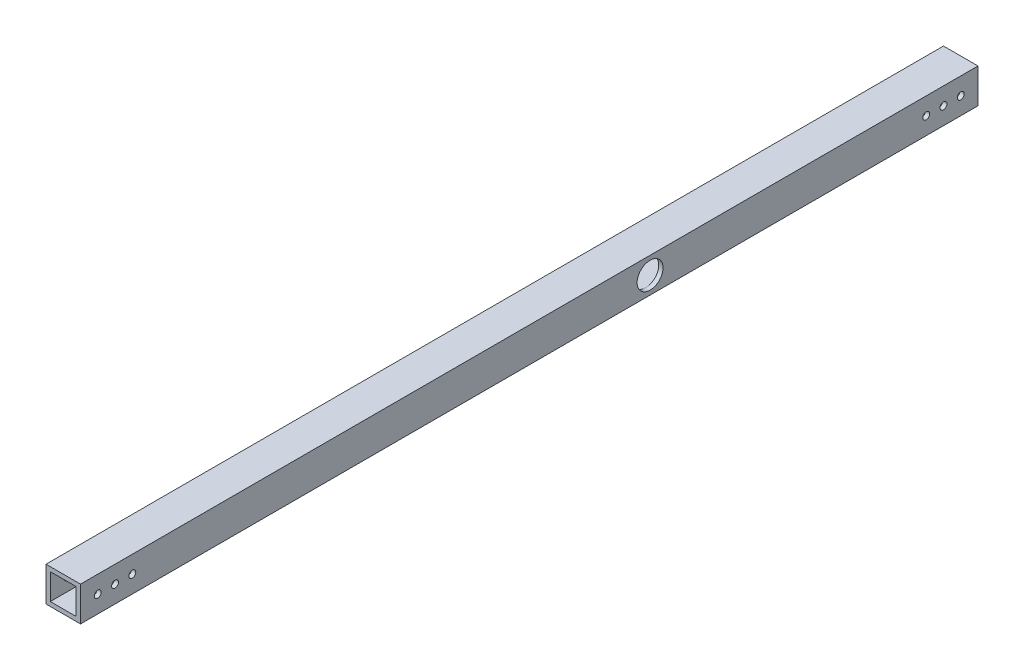
SolidWorks part; units mm, degrees
material "6061 Alloy"
ref_plane "Front" through (0, 0, 0) normal (0, 0, 1) x (1, 0, 0)
ref_plane "Top" through (0, 0, 0) normal (0, 1, 0) x (1, 0, 0)
ref_plane "Right" through (0, 0, 0) normal (1, 0, 0) x (0, 0, -1)
sketch "Sketch1" plane through (0, 0, 0) normal (0, 0, 1) x (1, 0, 0)
  line L1 (0, 0) -> (-25.4, 0)
  line L2 (0, 0) -> (0, 25.4)
  line L3 (0, 25.4) -> (-25.4, 25.4)
  line L4 (-25.4, 0) -> (-25.4, 25.4)
  dimension "D1" = 25.4
extrude "Extrude-Thin1" add sketch "Sketch1" along normal blind 660.4 thin
sketch "Sketch4" plane through (-25.4, 0, 0) normal (-1, 0, 0) x (0, 0, 1)
  line L0 (0, 25.4) -> (0, 0) construction
  line L1 (660.4, 0) -> (0, 0) construction
  circle A0 centre (241.3, 12.7) radius 9.525
  dimension "D1" = 241.3
  dimension "D2" = 12.7
  dimension "D3" = 19.05
extrude "Cut-Extrude1" cut sketch "Sketch4" against normal through all
hole_wizard "#10 Clearance Hole2" positions "Sketch5" profile "Sketch6" hole size "#10" standard "ANSI Inch" end condition through all
sketch "Sketch5" plane through (-25.4, 0, 0) normal (-1, 0, 0) x (0, 0, 1)
  line L1 (0, 25.4) -> (0, 0) construction
  line L2 (660.4, 0) -> (0, 0) construction
  point P0 (12.7, 12.7)
  point P2 (25.4, 12.7)
  point P4 (38.1, 12.7)
  dimension "D1" = 12.7
  dimension "D2" = 12.7
  dimension "D3" = 12.7
  dimension "D4" = 12.7
sketch "Sketch6" plane through (-25.4, 12.7, 12.7) normal (0, 1, 0) x (0, 0, 1)
  line L0 (0, 0) -> (0, 25.4)
  line L1 (0, 25.4) -> (2.5527, 25.4)
  line L2 (2.5527, 25.4) -> (2.5527, 0)
  line L5 (2.5527, 0) -> (0, 0)
  line L11 (0, -6.35) -> (0, 107.95) construction
  dimension "Thru Hole Dia." = 5.1054
  dimension "Thru Hole Depth" = 25.4
hole_wizard "#10 Clearance Hole3" positions "Sketch7" profile "Sketch8" hole size "#10" standard "ANSI Inch" end condition through all
sketch "Sketch7" plane through (-25.4, 0, 0) normal (-1, 0, 0) x (0, 0, 1)
  line L0 (660.4, 25.4) -> (660.4, 0) construction
  line L1 (660.4, 0) -> (0, 0) construction
  point P0 (622.3, 12.7)
  point P2 (635, 12.7)
  point P4 (647.7, 12.7)
  dimension "D1" = 12.7
  dimension "D2" = 12.7
  dimension "D3" = 12.7
  dimension "D4" = 12.7
sketch "Sketch8" plane through (-25.4, 12.7, 622.3) normal (0, 1, 0) x (0, 0, 1)
  line L0 (0, 0) -> (0, 25.4)
  line L1 (0, 25.4) -> (2.5527, 25.4)
  line L2 (2.5527, 25.4) -> (2.5527, 0)
  line L5 (2.5527, 0) -> (0, 0)
  line L11 (0, -6.35) -> (0, 107.95) construction
  dimension "Thru Hole Dia." = 5.1054
  dimension "Thru Hole Depth" = 25.4
